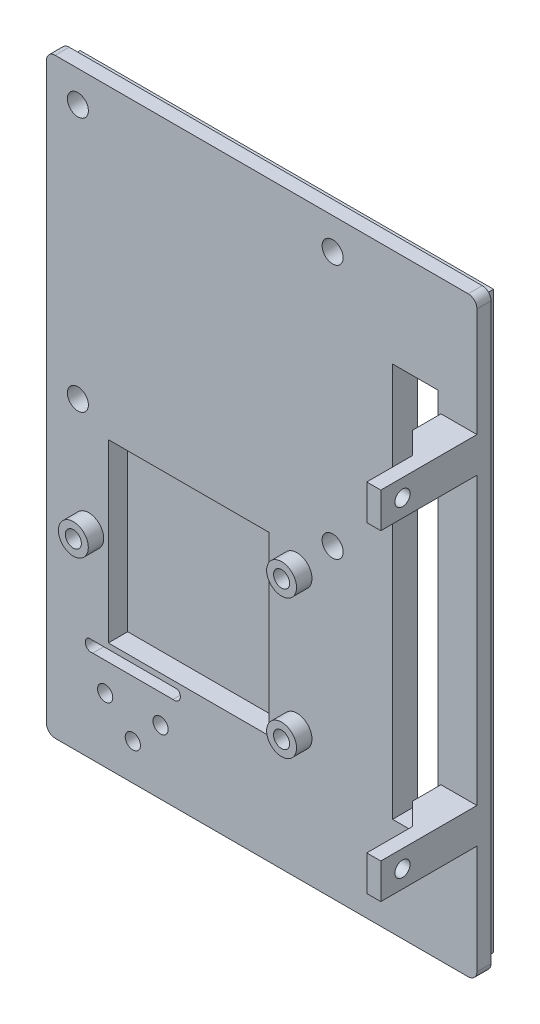
SolidWorks part; units mm, degrees
ref_plane "Front Plane" through (0, 0, 0) normal (0, 0, 1) x (1, 0, 0)
ref_plane "Top Plane" through (0, 0, 0) normal (0, 1, 0) x (1, 0, 0)
ref_plane "Right Plane" through (0, 0, 0) normal (1, 0, 0) x (0, 0, -1)
sketch "Sketch1" plane through (0, 0, 0) normal (0, 0, 1) x (1, 0, 0)
  line L1 (209.0037, -17.4643) -> (283.5853, -17.4643)
  line L3 (209.0037, -124.2713) -> (283.5853, -124.2713)
  line L6 (285.1601, -122.6965) -> (285.1601, -19.0391)
  line L8 (207.4289, -122.6965) -> (207.4289, -19.0391)
  arc A0 (207.4289, -19.0391) -> (209.0037, -17.4643) centre (209.0037, -19.0391) cw
  arc A1 (283.5853, -17.4643) -> (285.1601, -19.0391) centre (283.5853, -19.0391) cw
  arc A2 (285.1601, -122.6965) -> (283.5853, -124.2713) centre (283.5853, -122.6965) cw
  arc A3 (209.0037, -124.2713) -> (207.4289, -122.6965) centre (209.0037, -122.6965) cw
extrude "Boss-Extrude1" add sketch "Sketch1" along normal blind 2.54
sketch "Sketch2" plane through (0, 0, 0) normal (0, 0, -1) x (-1, 0, 0)
  line L1 (-208.9689, -122.7313) -> (-283.6201, -122.7313)
  line L2 (-208.9689, -122.7313) -> (-208.9689, -19.0043)
  line L3 (-208.9689, -19.0043) -> (-283.6201, -19.0043)
  line L4 (-283.6201, -122.7313) -> (-283.6201, -19.0043)
extrude "Boss-Extrude2" add sketch "Sketch2" along normal blind 2
sketch "Sketch3" plane through (0, 0, 2.54) normal (0, 0, 1) x (1, 0, 0)
  line L1 (214.9725, -105.5565) -> (231.0852, -105.5565)
  line L3 (215.7924, -107.5565) -> (230.2654, -107.5565)
  line L5 (207.4289, -19.0391) -> (207.4289, -122.6965) construction
  line L6 (209.0037, -124.2713) -> (283.5853, -124.2713) construction
  arc A0 (214.9725, -105.5565) -> (215.7924, -107.5565) centre (215.5414, -106.4913) ccw
  arc A1 (230.2654, -107.5565) -> (231.0852, -105.5565) centre (230.5163, -106.4913) ccw
  point P0 (214.5289, -106.9064)
  point P1 (231.5289, -106.9064)
  point P4 (215.5414, -106.4913)
  point P5 (230.5163, -106.4913)
  point P12 (223.0289, -107.5565)
  dimension "D1" = 17
  dimension "D2" = 2
  dimension "D3" = 15.6
  dimension "D4" = 17.78
extrude "Camera Ribbon Hole" cut sketch "Sketch3" against normal up to surface (4.54 mm away) up to face at (246.2945, -70.8678, -2)
sketch "Sketch4" plane through (0, 0, 2.54) normal (0, 0, 1) x (1, 0, 0)
  line L0 (218.5975, -72.7565) -> (247.5975, -72.7565)
  line L1 (219.0975, -104.0565) -> (247.0975, -104.0565) construction
  line L2 (219.0975, -104.0565) -> (219.0975, -73.2565) construction
  line L3 (219.0975, -73.2565) -> (247.0975, -73.2565) construction
  line L4 (247.0975, -104.0565) -> (247.0975, -73.2565) construction
  line L5 (247.5975, -104.5565) -> (247.5975, -72.7565)
  line L6 (218.5975, -104.5565) -> (247.5975, -104.5565)
  line L7 (218.5975, -104.5565) -> (218.5975, -72.7565)
  line L8 (231.0852, -105.5565) -> (214.9725, -105.5565) construction
  dimension "D4" = 28
  dimension "D5" = 30.8
  dimension "D7" = 1
  dimension "D6" = 0.5
extrude "RFD900 Hole" cut sketch "Sketch4" against normal blind 3.5
sketch "Sketch5" plane through (0, 0, 2.54) normal (0, 0, 1) x (1, 0, 0)
  line L0 (218.5975, -72.7565) -> (218.5975, -104.5565) construction
  circle A0 centre (215.071, -88.6565) radius 1.45
  circle A1 centre (215.071, -88.6565) radius 2.7
  circle A2 centre (252.671, -101.2065) radius 1.45
  circle A3 centre (252.671, -101.2065) radius 2.7
  circle A4 centre (252.671, -76.1065) radius 1.45
  circle A5 centre (252.671, -76.1065) radius 2.7
  point P24 (218.5975, -88.6565)
  dimension "D1" = 2.9
  dimension "D3" = 37.6
  dimension "D4" = 25.1
  dimension "D2" = 1.25
extrude "RFD900 Mount" add sketch "Sketch5" along normal blind 2.785
sketch "Sketch6" plane through (0, 0, 0) normal (0, 0, 1) x (1, 0, 0)
  line L0 (285.1601, -122.6965) -> (285.1601, -19.0391) construction
  line L1 (278.1257, -35.2632) -> (269.9236, -35.2632)
  line L2 (278.1257, -35.2632) -> (278.1257, -106.4723)
  line L3 (278.1257, -106.4723) -> (269.9236, -106.4723)
  line L4 (269.9236, -35.2632) -> (269.9236, -106.4723)
  point P6 (285.1601, -70.8678)
  point P7 (278.1257, -70.8678)
  dimension "D1" = 8.2021
  dimension "D2" = 71.2091
extrude "Wire Hole" cut sketch "Sketch6" along normal up to surface (4.54 mm away) from surface
sketch "Sketch7" plane through (0, 0, 2.54) normal (0, 0, 1) x (1, 0, 0)
  line L1 (285.1601, -38.6928) -> (278.6676, -38.6928)
  line L2 (285.1601, -38.6928) -> (285.1601, -45.0428)
  line L3 (285.1601, -45.0428) -> (278.6676, -45.0428)
  line L4 (278.6676, -38.6928) -> (278.6676, -45.0428)
  line L6 (285.1601, -96.6928) -> (278.6676, -96.6928)
  line L7 (285.1601, -96.6928) -> (285.1601, -103.0428)
  line L8 (285.1601, -103.0428) -> (278.6676, -103.0428)
  line L9 (278.6676, -96.6928) -> (278.6676, -103.0428)
  line L10 (285.1601, -122.6965) -> (285.1601, -19.0391) construction
  line L11 (281.9138, -45.0428) -> (281.9138, -96.6928) construction
  point P8 (285.1601, -70.8678)
  point P11 (281.9138, -70.8678)
  dimension "D1" = 6.35
  dimension "D2" = 6.4925
  dimension "D3" = 64.35
extrude "Boss-Extrude4" add sketch "Sketch7" along normal blind 17.36
sketch "Sketch8" plane through (0, -103.0428, 0) normal (0, -1, 0) x (1, 0, 0)
  line L1 (278.6676, 19.9) -> (285.1601, 19.9) construction
  line L3 (282.6248, 11.685) -> (278.6676, 7.7277)
  line L4 (278.6676, 19.9) -> (278.6676, 2.54) construction
  line L6 (274.4753, 16.98) -> (286.1182, 16.98) construction
  line L8 (274.4532, 14.605) -> (286.0962, 14.605) construction
  line L9 (197.2321, 28.0757) -> (197.2583, 25.0759) construction
  line L10 (282.6248, 19.9) -> (282.6248, 16.98)
  line L12 (278.6676, 7.7277) -> (278.6676, 19.9)
  line L13 (278.6676, 19.9) -> (282.6248, 19.9)
  line L14 (282.6248, 14.605) -> (282.6248, 11.685)
  line L15 (282.6248, 16.98) -> (282.6248, 14.605)
  line L16 (197.6028, 25.0791) -> (197.5757, 28.179) construction
  dimension "D2" = 45
extrude "Cut-Extrude4" cut sketch "Sketch8" against normal up to surface (64.35 mm away) up to face at (281.9138, -38.6928, 11.22)
sketch "Sketch11" plane through (285.1601, 0, 0) normal (-1, 0, 0) x (0, 0, 1)
  circle A0 centre (15.98, -99.8678) radius 1.375
  circle A1 centre (15.98, -41.8678) radius 1.375
  dimension "D1" = 2.75
sketch "Sketch13" plane through (285.1601, 0, 0) normal (1, 0, 0) x (0, 0, -1)
  circle A0 centre (-15.98, -99.8678) radius 1.375
  circle A1 centre (-15.98, -41.8678) radius 1.375
  dimension "D1" = 2.75
  dimension "D2" = 2.75
extrude "Cut-Extrude7" cut sketch "Sketch13" against normal up to surface (2.5353 mm away) up to face at (282.6248, -99.8678, 15.7925)
sketch "Sketch12" plane through (0, 0, 2.54) normal (0, 0, 1) x (1, 0, 0)
  circle A0 centre (252.671, -76.1065) radius 1.45
  circle A1 centre (252.671, -101.2065) radius 1.45
  circle A2 centre (215.071, -88.6565) radius 1.45
extrude "Cut-Extrude6" cut sketch "Sketch12" against normal up to surface (4.54 mm away) up to face at (274.0247, -70.8678, -2)
sketch "Sketch15" plane through (0, 0, 2.54) normal (0, 0, 1) x (1, 0, 0)
  line L0 (213.1039, -23.1393) -> (259.1039, -23.1393) construction
  line L1 (210.6039, -71.6393) -> (261.6039, -71.6393) construction
  line L2 (210.6039, -71.6393) -> (210.6039, -20.6393) construction
  line L3 (210.6039, -20.6393) -> (261.6039, -20.6393) construction
  line L4 (261.6039, -71.6393) -> (261.6039, -20.6393) construction
  line L5 (213.1039, -23.1393) -> (213.1039, -69.1393) construction
  line L6 (207.4289, -19.0391) -> (207.4289, -122.6965) construction
  line L7 (283.5853, -17.4643) -> (209.0037, -17.4643) construction
  circle A0 centre (213.1039, -23.1393) radius 1.9
  circle A1 centre (259.1039, -23.1393) radius 1.9
  circle A2 centre (213.1039, -69.1393) radius 1.9
  circle A3 centre (259.1039, -69.1393) radius 1.9
  point P8 (236.1039, -23.1393)
  point P11 (236.1039, -20.6393)
  point P14 (213.1039, -46.1393)
  point P15 (210.6039, -46.1393)
  dimension "D3" = 3.8
  dimension "D1" = 51
  dimension "D2" = 51
  dimension "D4" = 46
  dimension "D5" = 46
  dimension "D6" = 3.175
  dimension "D7" = 3.175
extrude "Cut-Extrude8" cut sketch "Sketch15" against normal up to surface (4.54 mm away) up to face at (251.221, -76.1065, -2)
sketch "Sketch16" plane through (0, 0, 2.54) normal (0, 0, 1) x (1, 0, 0)
  circle A0 centre (228.0289, -112.6965) radius 1.375
  circle A1 centre (223.0289, -117.6965) radius 1.375
  circle A2 centre (218.0289, -112.6965) radius 1.375
extrude "Cut-Extrude9" cut sketch "Sketch16" against normal up to surface (4.54 mm away) up to face at (257.2039, -69.1393, -2)
